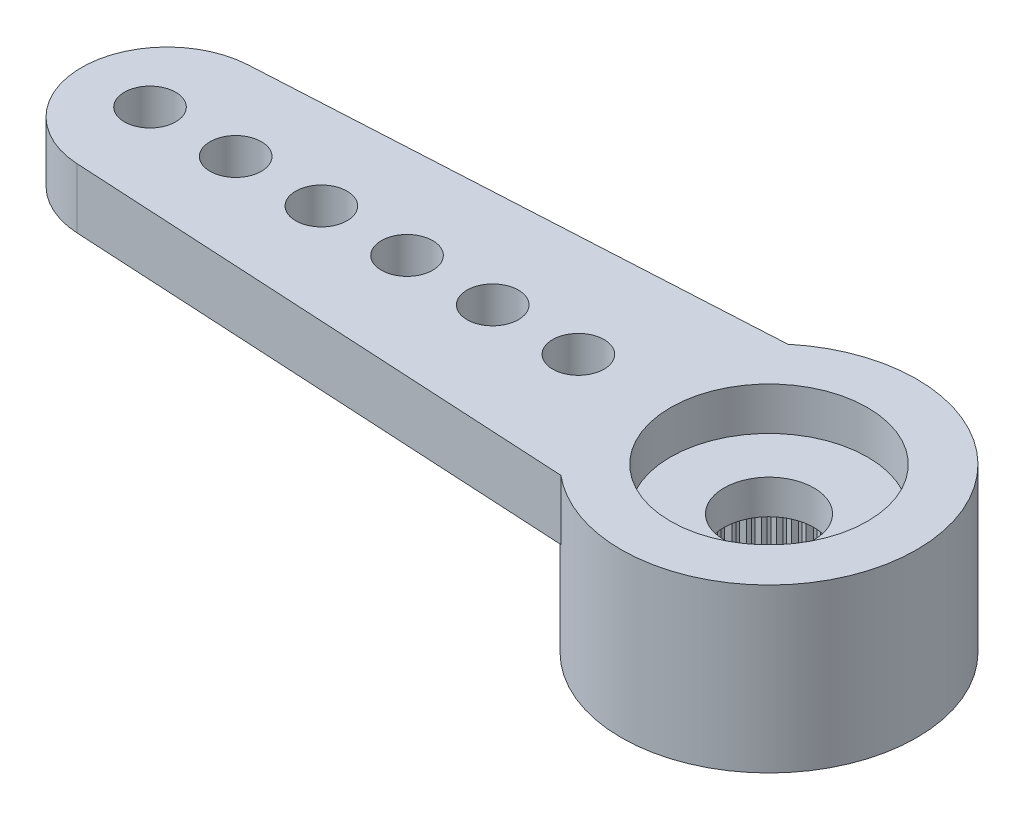
SolidWorks part; units mm, degrees
material "PVC Rígido"
ref_plane "Plano frontal" through (0, 0, 0) normal (0, 0, 1) x (1, 0, 0)
ref_plane "Plano superior" through (0, 0, 0) normal (0, 1, 0) x (1, 0, 0)
ref_plane "Plano direito" through (0, 0, 0) normal (1, 0, 0) x (0, 0, -1)
sketch "Esboço1" plane through (0, 0, 0) normal (0, 1, 0) x (1, 0, 0)
  line L0 (0, 0) -> (-14.05, 0) construction
  line L1 (-14.1591, 1.997) -> (-2.2091, 2.65)
  line L2 (-2.2091, -2.65) -> (-14.1591, -1.997)
  arc A0 (-2.2091, -2.65) -> (-2.2091, 2.65) centre (0, 0) ccw
  arc A1 (-14.1591, 1.997) -> (-14.1591, -1.997) centre (-14.05, 0) ccw
  dimension "D1" = 6.9
  dimension "D2" = 4
  dimension "D3" = 19.5
  dimension "D4" = 5.3
  dimension "D5" = 11.8409
extrude "Ressalto-extrusão1" add sketch "Esboço1" against normal blind 1.4
sketch "Esboço2" plane through (0, -1.4, 0) normal (0, -1, 0) x (1, 0, 0)
  arc A0 (-2.2091, -2.65) -> (-2.2091, 2.65) centre (0, 0) ccw construction
  circle A1 centre (0, 0) radius 3.45
extrude "Ressalto-extrusão2" add sketch "Esboço2" along normal offset from surface (2.4 mm away) 3.8 up to face at (-7.242, 0, 0)
hole_wizard "Furo4" positions "Esboço9" profile "Esboço10" legacy end condition through all
sketch "Esboço9" plane through (0, 0, 0) normal (0, 1, 0) x (1, 0, 0)
  line L1 (-14.45, 0) -> (0, 0) construction
  arc A2 (-14.1591, 1.997) -> (-14.1591, -1.997) centre (-14.05, 0) ccw construction
  point P0 (-14.45, 0)
  point P19 (-16.05, 0)
  dimension "D1" = 1.6
sketch "Esboço10" plane through (-14.45, 0, 0) normal (1, 0, 0) x (0, 0, 1)
  line L0 (0, 0) -> (0, 3.8)
  line L1 (0, 3.8) -> (0.6, 3.8)
  line L2 (0.6, 3.8) -> (0.6, 0)
  line L3 (0.6, 0) -> (0, 0)
  line L4 (0, 110) -> (0, -10) construction
  dimension "Diameter" = 1.2
  dimension "Depth" = 3.8
pattern_linear "Padrão linear1" count 6 spacing 2 along (1, 0, 0) of "Furo4"
hole_wizard "Furo1" positions "Esboço3" profile "Esboço4" legacy
sketch "Esboço3" plane through (0, -3.8, 0) normal (0, -1, 0) x (-1, 0, 0)
  point P0 (0, 0)
sketch "Esboço4" plane through (0, -3.8, 0) normal (1, 0, 0) x (0, 0, -1)
  line L0 (0, 0) -> (0, 2)
  line L1 (0, 2) -> (2.475, 2)
  line L2 (2.475, 2) -> (2.475, 0)
  line L3 (2.475, 0) -> (0, 0)
  line L4 (0, 110) -> (0, -10) construction
  dimension "Diameter" = 4.95
  dimension "Depth" = 2
hole_wizard "Furo2" positions "Esboço5" profile "Esboço6" legacy
sketch "Esboço5" plane through (0, 0, 0) normal (0, 1, 0) x (1, 0, 0)
  point P0 (0, 0)
sketch "Esboço6" plane through (0, 0, 0) normal (1, 0, 0) x (0, 0, 1)
  line L0 (0, 0) -> (0, 1)
  line L1 (0, 1) -> (2.3, 1)
  line L2 (2.3, 1) -> (2.3, 0)
  line L3 (2.3, 0) -> (0, 0)
  line L4 (0, 110) -> (0, -10) construction
  dimension "Diameter" = 4.6
  dimension "Depth" = 1
hole_wizard "Furo3" positions "Esboço7" profile "Esboço8" legacy end condition through all
sketch "Esboço7" plane through (0, 0, 0) normal (0, 1, 0) x (1, 0, 0)
  point P0 (0, 0)
sketch "Esboço8" plane through (0, 0, 0) normal (1, 0, 0) x (0, 0, 1)
  line L0 (0, 0) -> (0, 3.8)
  line L1 (0, 3.8) -> (1.05, 3.8)
  line L2 (1.05, 3.8) -> (1.05, 0)
  line L3 (1.05, 0) -> (0, 0)
  line L4 (0, 110) -> (0, -10) construction
  dimension "Diameter" = 2.1
  dimension "Depth" = 3.8
sketch "Esboço11" plane through (0, -3.8, 0) normal (0, -1, 0) x (1, 0, 0)
  line L0 (-0.0981, 2.4731) -> (0, 2.375)
  line L1 (0, 2.375) -> (0.0981, 2.4731)
  line L2 (0, 0) -> (0, 2.475) construction
  circle A0 centre (0, 0) radius 2.375 construction
  circle A1 centre (0, 0) radius 2.475
  arc A2 (0.0981, 2.4731) -> (-0.0981, 2.4731) centre (0, 0) ccw
  dimension "D3" = 4.75
  dimension "D2" = 0.1
  dimension "D1" = 0
extrude "Ressalto-extrusão3" add sketch "Esboço11" against normal up to surface (2 mm away) up to face at (0, -1.8, 1.05)
pattern_circular "PadrãoCircular1" count 60 over 360 about axis through (0, 0, 0) along (0, 1, 0) of "Ressalto-extrusão3"
